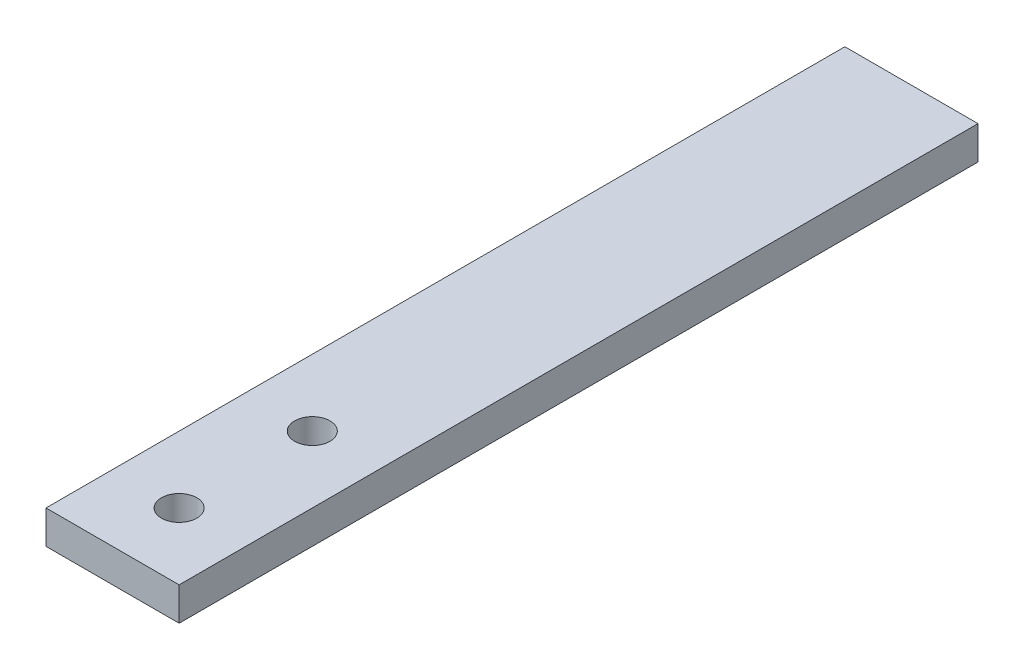
SolidWorks part; units mm, degrees
ref_plane "Front Plane" through (0, 0, 0) normal (0, 0, 1) x (1, 0, 0)
ref_plane "Top Plane" through (0, 0, 0) normal (0, 1, 0) x (1, 0, 0)
ref_plane "Right Plane" through (0, 0, 0) normal (1, 0, 0) x (0, 0, -1)
sketch "Sketch1" plane through (0, 0, 0) normal (0, 1, 0) x (1, 0, 0)
  line L1 (-12.7, -76.2) -> (12.7, -76.2)
  line L2 (-12.7, -76.2) -> (-12.7, 76.2)
  line L3 (-12.7, 76.2) -> (12.7, 76.2)
  line L4 (12.7, -76.2) -> (12.7, 76.2)
  line L5 (-12.7, -76.2) -> (12.7, 76.2) construction
  line L6 (-12.7, 76.2) -> (12.7, -76.2) construction
  point P0 (0, 0)
  dimension "D1" = 25.4
  dimension "D2" = 152.4
extrude "Boss-Extrude1" add sketch "Sketch1" along normal mid plane 6.35 contours L3 L4 L1 L2
sketch "Sketch2" plane through (0, 3.175, 0) normal (0, 1, 0) x (1, 0, 0)
  line L0 (0, -3.4925) -> (0, 3.4925) construction
  line L1 (-12.7, -76.2) -> (12.7, -76.2) construction
  point P0 (0, -63.5)
  point P1 (0, -38.1)
  point P4 (0, 0)
  point P6 (0, 0)
  point P7 (0, -54.104)
  dimension "D1" = 25.4
  dimension "D2" = 12.7
hole_wizard "1/4 Clearance Hole1" positions "Sketch3" profile "Sketch4" hole size "1/4" standard "ANSI Inch" end condition through all
sketch "Sketch3" plane through (0, 3.175, 0) normal (0, 1, 0) x (1, 0, 0)
  point P3 (0, -63.5)
  point P8 (0, -38.1)
sketch "Sketch4" plane through (0, 3.175, 63.5) normal (1, 0, 0) x (0, 0, 1)
  line L0 (0, 0) -> (0, 6.35)
  line L1 (0, 6.35) -> (3.3782, 6.35)
  line L2 (3.3782, 6.35) -> (3.3782, 0)
  line L5 (3.3782, 0) -> (0, 0)
  line L11 (0, -6.35) -> (0, 107.95) construction
  dimension "Thru Hole Dia." = 6.7564
  dimension "Thru Hole Depth" = 6.35
